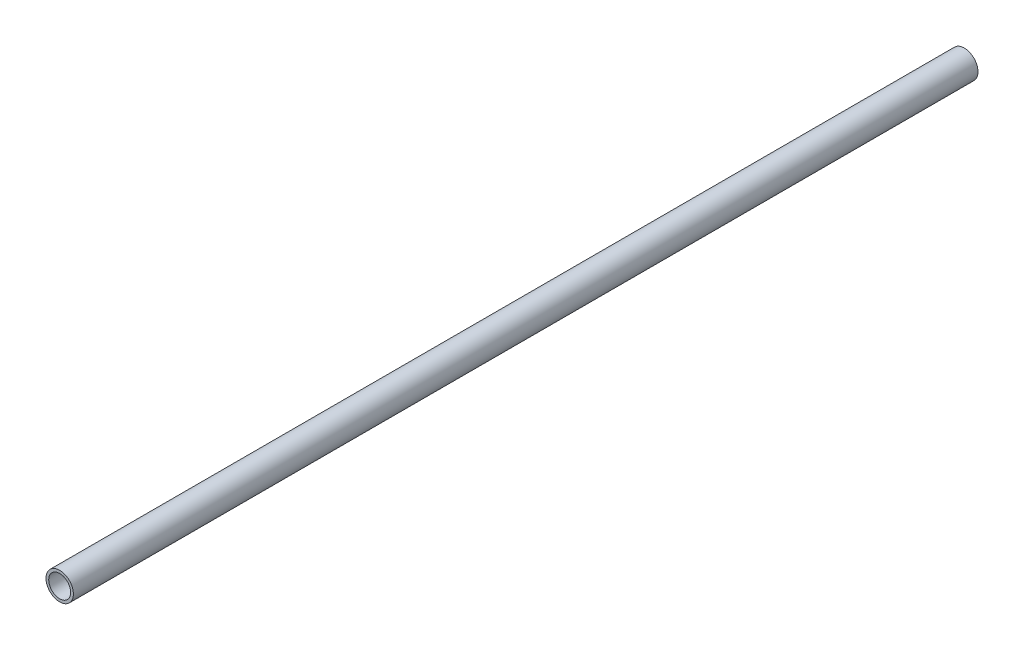
SolidWorks part; units mm, degrees
ref_plane "Ebene vorne" through (0, 0, 0) normal (0, 0, 1) x (1, 0, 0)
ref_plane "Ebene oben" through (0, 0, 0) normal (0, 1, 0) x (1, 0, 0)
ref_plane "Ebene rechts" through (0, 0, 0) normal (1, 0, 0) x (0, 0, -1)
sketch "Skizze1" plane through (0, 0, 0) normal (0, 0, 1) x (1, 0, 0)
  circle A0 centre (0, 0) radius 4
  circle A1 centre (0, 0) radius 5
  dimension "D1" = 8
  dimension "D2" = 10
extrude "Aufsatz-Linear austragen1" add sketch "Skizze1" along normal blind 330
